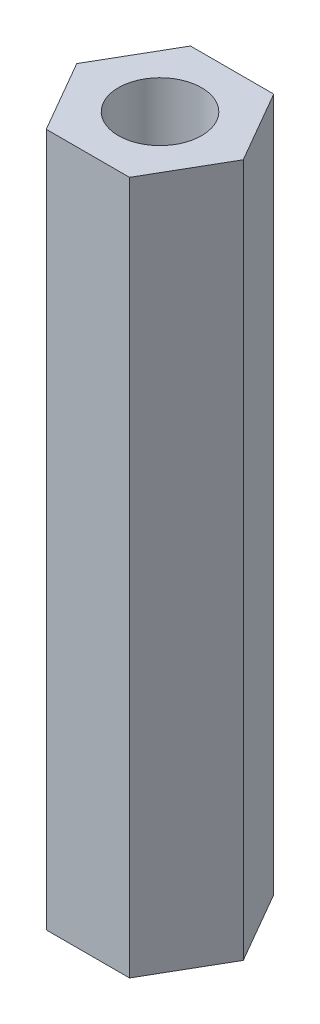
SolidWorks part; units mm, degrees
other "Markup1"
sketch "Sketch2" plane through (-3.0022, 25, -2.6) normal (0, 1, 0) x (1, 0, 0)
material "Brass"
ref_plane "Front Plane" through (0, 0, 0) normal (0, 0, 1) x (1, 0, 0)
ref_plane "Top Plane" through (0, 0, 0) normal (0, 1, 0) x (1, 0, 0)
ref_plane "Right Plane" through (0, 0, 0) normal (1, 0, 0) x (0, 0, -1)
sketch "Sketch1" plane through (0, 0, 0) normal (0, 1, 0) x (1, 0, 0)
  line L1 (3.0022, 0) -> (1.5011, 2.6)
  line L2 (1.5011, 2.6) -> (-1.5011, 2.6)
  line L3 (-1.5011, 2.6) -> (-3.0022, 0)
  line L4 (-3.0022, 0) -> (-1.5011, -2.6)
  line L5 (-1.5011, -2.6) -> (1.5011, -2.6)
  line L6 (1.5011, -2.6) -> (3.0022, 0)
  circle A0 centre (0, 0) radius 1.5
  circle A1 centre (0, 0) radius 2.6 construction
  dimension "D1" = 5.2
extrude "Boss-Extrude1" add sketch "Sketch1" along normal blind 25
